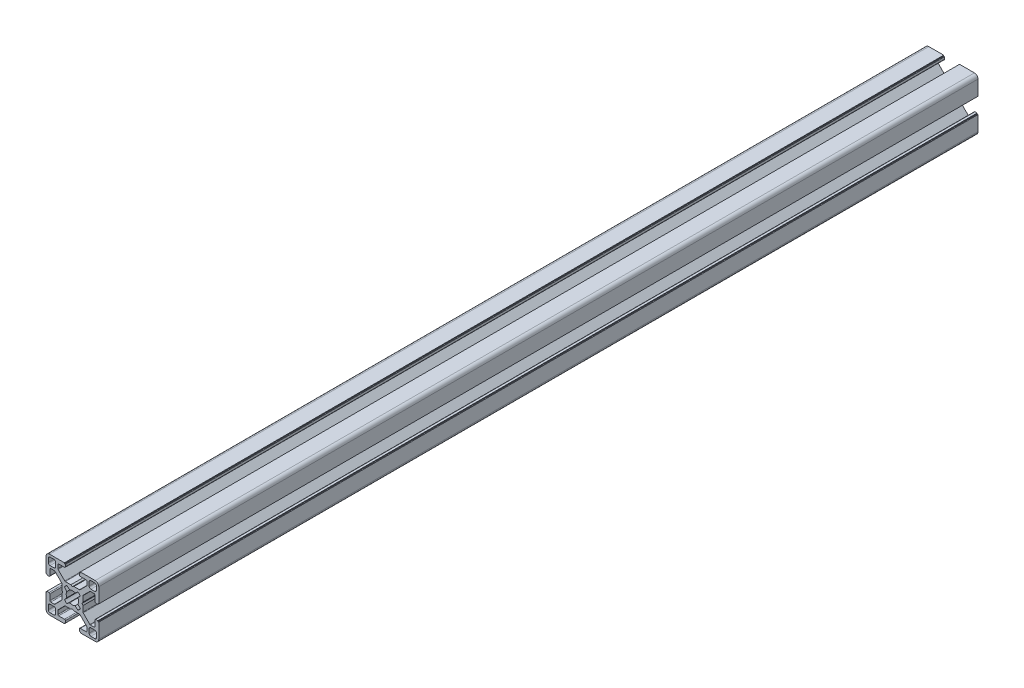
SolidWorks part; units mm, degrees
ref_plane "Front Plane" through (0, 0, 0) normal (0, 0, 1) x (1, 0, 0)
ref_plane "Top Plane" through (0, 0, 0) normal (0, 1, 0) x (1, 0, 0)
ref_plane "Right Plane" through (0, 0, 0) normal (1, 0, 0) x (0, 0, -1)
sketch "Sketch1" plane through (0, 0, 0) normal (0, 0, 1) x (1, 0, 0)
  line L0 (-15, 0) -> (15, 0) construction
  line L1 (0, -15) -> (0, 15) construction
  line L2 (-4.5, 15) -> (4.5, 15) construction
  line L3 (-4, -15) -> (4, -15) construction
  line L4 (-4.5, 15) -> (-4.5, 14.5)
  line L5 (-4.5, 14.5) -> (-4, 14.5)
  line L6 (-4, 14.5) -> (-4, 13.29)
  line L7 (-4.5, 12.79) -> (-7.7675, 12.79)
  line L8 (-8.2675, 12.29) -> (-8.2675, 10.2707)
  line L9 (-8.1211, 9.9171) -> (-4.3504, 6.1464)
  line L10 (-3.9968, 6) -> (0, 6)
  line L11 (0, 0) -> (-15, 15) construction
  line L12 (-4.5, 15) -> (-12.968, 15)
  line L14 (-12.705, 9.5135) -> (-10.5135, 9.5135)
  line L15 (-13.705, 10.5135) -> (-13.705, 12.705)
  line L16 (-12.705, 13.705) -> (-10.5135, 13.705)
  line L17 (-9.5135, 10.5135) -> (-9.5135, 12.705)
  line L18 (-13.705, 9.5135) -> (-9.5135, 13.705) construction
  line L19 (-13.705, 13.705) -> (-9.5135, 9.5135) construction
  line L20 (-3.1568, 4.5038) -> (-1.5303, 3.1477) construction
  line L21 (-4.5038, 3.1568) -> (-3.1477, 1.5303) construction
  line L22 (-6, 3.9968) -> (-6, 0)
  line L23 (-9.9171, 8.1211) -> (-6.1464, 4.3504)
  line L24 (-15, 4.5) -> (-15, 12.968)
  line L25 (-12.29, 8.2675) -> (-10.2707, 8.2675)
  line L26 (-12.79, 4.5) -> (-12.79, 7.7675)
  line L27 (-14.5, 4) -> (-13.29, 4)
  line L28 (-14.5, 4.5) -> (-14.5, 4)
  line L29 (-15, 4.5) -> (-14.5, 4.5)
  circle A0 centre (0, 0) radius 3.5
  arc A1 (-12.968, 15) -> (-15, 12.968) centre (-12.968, 12.968) ccw
  circle A2 centre (0, 0) radius 5.5 construction
  arc A3 (-10.5135, 9.5135) -> (-9.5135, 10.5135) centre (-10.5135, 10.5135) ccw
  arc A4 (-13.705, 12.705) -> (-12.705, 13.705) centre (-12.705, 12.705) cw
  arc A5 (-10.5135, 13.705) -> (-9.5135, 12.705) centre (-10.5135, 12.705) cw
  arc A6 (-12.705, 9.5135) -> (-13.705, 10.5135) centre (-12.705, 10.5135) cw
  arc A7 (-12.79, 4.5) -> (-13.29, 4) centre (-13.29, 4.5) cw
  arc A8 (-12.29, 8.2675) -> (-12.79, 7.7675) centre (-12.29, 7.7675) ccw
  arc A9 (-9.9171, 8.1211) -> (-10.2707, 8.2675) centre (-10.2707, 7.7675) ccw
  arc A10 (-6, 3.9968) -> (-6.1464, 4.3504) centre (-6.5, 3.9968) ccw
  arc A11 (-4.3504, 6.1464) -> (-3.9968, 6) centre (-3.9968, 6.5) ccw
  arc A12 (-4, 13.29) -> (-4.5, 12.79) centre (-4.5, 13.29) cw
  arc A13 (-7.7675, 12.79) -> (-8.2675, 12.29) centre (-7.7675, 12.29) ccw
  arc A14 (-8.2675, 10.2707) -> (-8.1211, 9.9171) centre (-7.7675, 10.2707) ccw
  point P4 (0, 0)
  point P8 (0, 0)
  point P13 (0, 15)
  point P15 (0, -15)
  point P16 (0, 6)
  point P23 (-11.6092, 11.6093)
  point P26 (0, 6)
  point P62 (-12.79, 4)
  point P65 (-12.79, 8.2675)
  point P68 (-10.0636, 8.2675)
  point P71 (-6, 4.2039)
  point P74 (-4.2039, 6)
  point P77 (-4, 12.79)
  point P80 (-8.2675, 12.79)
  point P83 (-8.2675, 10.0636)
  dimension "Center Hole Diameter" = 7
  dimension "D11" = 2.032
  dimension "D9" = 11
  dimension "D13" = 1
  dimension "D14" = 0.5
  dimension "Rail Height" = 30
  dimension "Rail Width" = 30
  dimension "T-Slot Width" = 8
  dimension "T-Slot Depth" = 9
  dimension "D1" = 9
  dimension "D2" = 45
  dimension "D3" = 8
  dimension "D4" = 2.21
  dimension "D5" = 16.535
  dimension "D7" = 2.54
  dimension "D6" = 1.295
  dimension "D8" = 1.246
  dimension "D10" = 10.36
  dimension "D12" = 1.905
sketch "Sketch2" plane through (0, 0, 0) normal (1, 0, 0) x (0, 0, -1)
  line L0 (-76.2, 0) -> (76.2, 0) construction
  line L2 (0, -15) -> (0, 15) construction
  line L3 (0, -15) -> (0, 15) construction
  line L4 (-76.2, -15) -> (-76.2, 15) construction
  line L5 (76.2, -15) -> (76.2, 15) construction
  point P0 (-38.7, 0)
  point P3 (0, 0)
  point P4 (38.7, 0)
  point P12 (-76.2, 0)
  point P14 (76.2, 0)
  dimension "Length" = 152.4
  dimension "D1" = 37.5
sketch "Sketch3" plane through (0, 0, 0) normal (0, 0, 1) x (1, 0, 0)
  line L0 (-4.5038, 3.1568) -> (-3.1477, 1.5303)
  line L1 (0, 3.5) -> (0, 5.5)
  line L2 (-5.5, 0) -> (-3.5, 0)
  line L7 (-6, 3.9968) -> (-6, 0) construction
  line L31 (-9.9171, 8.1211) -> (-6.1464, 4.3504) construction
  line L117 (-12.29, 8.2675) -> (-10.2707, 8.2675) construction
  line L118 (-12.79, 4.5) -> (-12.79, 7.7675) construction
  line L157 (-12.705, 9.5135) -> (-10.5135, 9.5135)
  line L158 (-9.5135, 10.5135) -> (-9.5135, 12.705)
  line L163 (-10.5135, 13.705) -> (-12.705, 13.705)
  line L164 (-13.705, 12.705) -> (-13.705, 10.5135)
  line L165 (-12.705, 9.5135) -> (-10.5135, 9.5135)
  line L166 (-9.5135, 10.5135) -> (-9.5135, 12.705)
  line L167 (-10.5135, 13.705) -> (-12.705, 13.705)
  line L168 (-13.705, 12.705) -> (-13.705, 10.5135)
  line L169 (-14.5, 4) -> (-13.29, 4) construction
  line L170 (-14.5, 4.5) -> (-14.5, 4) construction
  line L171 (-15, 4.5) -> (-14.5, 4.5) construction
  line L172 (-15, 4.5) -> (-15, 12.968) construction
  line L173 (-4.5, 15) -> (-12.968, 15) construction
  line L174 (-4.5, 15) -> (-4.5, 14.5) construction
  line L175 (-4.5, 14.5) -> (-4, 14.5) construction
  line L176 (-4, 14.5) -> (-4, 13.29) construction
  line L177 (-4.5, 12.79) -> (-7.7675, 12.79) construction
  line L178 (-8.2675, 12.29) -> (-8.2675, 10.2707) construction
  line L179 (-8.1211, 9.9171) -> (-4.3504, 6.1464) construction
  line L180 (-3.9968, 6) -> (0, 6) construction
  line L181 (-6, 3.9968) -> (-6, 0.866)
  line L182 (-9.9171, 8.1211) -> (-6.1464, 4.3504)
  line L183 (-12.29, 8.2675) -> (-10.2707, 8.2675)
  line L184 (-12.79, 4.5) -> (-12.79, 7.7675)
  line L185 (-14.5, 4) -> (-13.29, 4)
  line L186 (-14.5, 4.5) -> (-14.5, 4)
  line L187 (-15, 4.5) -> (-14.5, 4.5)
  line L188 (-15, 4.5) -> (-15, 12.968)
  line L189 (-4.5, 15) -> (-12.968, 15)
  line L190 (-4.5, 15) -> (-4.5, 14.5)
  line L191 (-4.5, 14.5) -> (-4, 14.5)
  line L192 (-4, 14.5) -> (-4, 13.29)
  line L193 (-4.5, 12.79) -> (-7.7675, 12.79)
  line L194 (-8.2675, 12.29) -> (-8.2675, 10.2707)
  line L195 (-8.1211, 9.9171) -> (-4.3504, 6.1464)
  line L196 (-3.9968, 6) -> (-0.866, 6)
  line L197 (-0.866, 6) -> (0, 5.5)
  line L198 (0, -15) -> (0, 15) construction
  line L199 (0, 0) -> (-15, 15) construction
  line L200 (0, 0) -> (-15, 15) construction
  line L201 (-3.1568, 4.5038) -> (-1.5303, 3.1477) construction
  line L202 (-3.1568, 4.5038) -> (-1.5303, 3.1477)
  line L203 (-6, 0.866) -> (-5.5, 0)
  line L204 (-15, 0) -> (15, 0) construction
  line L205 (-15, 0) -> (15, 0) construction
  line L206 (0, -15) -> (0, 15) construction
  arc A0 (-3.5, 0) -> (-3.1477, 1.5303) centre (0, 0) cw
  arc A10 (-6, 3.9968) -> (-6.1464, 4.3504) centre (-6.5, 3.9968) ccw construction
  circle A16 centre (0, 0) radius 3.5
  arc A18 (0, 3.5) -> (-1.5303, 3.1477) centre (0, 0) ccw
  arc A20 (-9.9171, 8.1211) -> (-10.2707, 8.2675) centre (-10.2707, 7.7675) ccw construction
  arc A22 (-12.29, 8.2675) -> (-12.79, 7.7675) centre (-12.29, 7.7675) ccw construction
  arc A28 (-13.29, 4) -> (-12.79, 4.5) centre (-13.29, 4.5) ccw construction
  arc A29 (-10.5135, 9.5135) -> (-9.5135, 10.5135) centre (-10.5135, 10.5135) ccw
  arc A30 (-9.5135, 12.705) -> (-10.5135, 13.705) centre (-10.5135, 12.705) ccw
  arc A31 (-12.705, 13.705) -> (-13.705, 12.705) centre (-12.705, 12.705) ccw
  arc A32 (-13.705, 10.5135) -> (-12.705, 9.5135) centre (-12.705, 10.5135) ccw
  arc A33 (-10.5135, 9.5135) -> (-9.5135, 10.5135) centre (-10.5135, 10.5135) ccw
  arc A34 (-9.5135, 12.705) -> (-10.5135, 13.705) centre (-10.5135, 12.705) ccw
  arc A35 (-12.705, 13.705) -> (-13.705, 12.705) centre (-12.705, 12.705) ccw
  arc A36 (-13.705, 10.5135) -> (-12.705, 9.5135) centre (-12.705, 10.5135) ccw
  arc A37 (-12.968, 15) -> (-15, 12.968) centre (-12.968, 12.968) ccw construction
  arc A38 (-4.5, 12.79) -> (-4, 13.29) centre (-4.5, 13.29) ccw construction
  arc A39 (-7.7675, 12.79) -> (-8.2675, 12.29) centre (-7.7675, 12.29) ccw construction
  arc A40 (-8.2675, 10.2707) -> (-8.1211, 9.9171) centre (-7.7675, 10.2707) ccw construction
  arc A41 (-4.3504, 6.1464) -> (-3.9968, 6) centre (-3.9968, 6.5) ccw construction
  arc A42 (-6, 3.9968) -> (-6.1464, 4.3504) centre (-6.5, 3.9968) ccw
  arc A43 (-9.9171, 8.1211) -> (-10.2707, 8.2675) centre (-10.2707, 7.7675) ccw
  arc A44 (-12.29, 8.2675) -> (-12.79, 7.7675) centre (-12.29, 7.7675) ccw
  arc A45 (-13.29, 4) -> (-12.79, 4.5) centre (-13.29, 4.5) ccw
  arc A46 (-12.968, 15) -> (-15, 12.968) centre (-12.968, 12.968) ccw
  arc A47 (-4.5, 12.79) -> (-4, 13.29) centre (-4.5, 13.29) ccw
  arc A48 (-7.7675, 12.79) -> (-8.2675, 12.29) centre (-7.7675, 12.29) ccw
  arc A49 (-8.2675, 10.2707) -> (-8.1211, 9.9171) centre (-7.7675, 10.2707) ccw
  arc A50 (-4.3504, 6.1464) -> (-3.9968, 6) centre (-3.9968, 6.5) ccw
  circle A51 centre (0, 0) radius 5.5 construction
  arc A52 (-3.1568, 4.5038) -> (-4.5038, 3.1568) centre (0, 0) ccw
  dimension "D3" = 60
  dimension "D4" = 60
  dimension "D1" = 0
  dimension "D2" = 0
extrude "Boss-Extrude1" add sketch "Sketch3" along normal mid plane 500
pattern_circular "CirPattern1" count 4 over 360 about axis through (0, 0, 0) along (0, 0, 1) of "Boss-Extrude1"
ref_plane "Contact Plane1" through (15, 0, 0) normal (1, 0, 0) x (0, 0, -1)
ref_plane "Contact Plane2" through (0, -15, 0) normal (0, 1, 0) x (1, 0, 0)
ref_plane "Contact Plane3" through (-15, 0, 0) normal (1, 0, 0) x (0, 0, -1)
ref_plane "Contact Plane4" through (0, 15, 0) normal (0, 1, 0) x (1, 0, 0)
equation "\"D1@Sketch2\" = \"Rail Height@Sketch1\" * 1.25"
equation "\"D1@Sketch1\"=\"T-Slot Width@Sketch1\"+1mm"
equation "\"D3@Sketch1\"=\"T-Slot Width@Sketch1\""
equation "\"D1@Boss-Extrude1\"=\"Length\""
equation "\"Length\" = 500mm"
